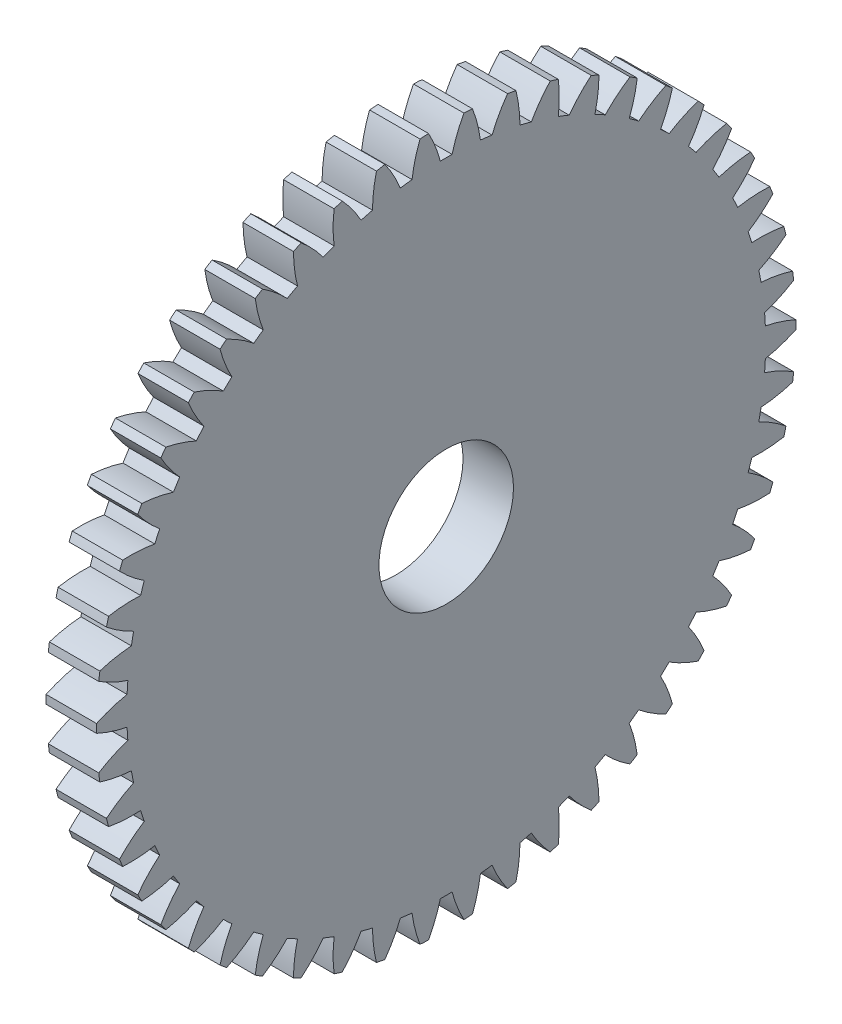
SolidWorks part; units mm, degrees
ref_plane "Plane1" through (0, 0, 0) normal (0, 0, 1) x (1, 0, 0)
ref_plane "Plane2" through (0, 0, 0) normal (0, 1, 0) x (1, 0, 0)
ref_plane "Plane3" through (0, 0, 0) normal (1, 0, 0) x (0, 0, -1)
sketch "HoldingSke" plane through (0, 0, 0) normal (0, 1, 0) x (1, 0, 0)
  line L0 (0, 0) -> (0.8035, -0.9576)
  line L1 (-15, 0) -> (100, 0) construction
  line L2 (0, 0) -> (-2.1039, 2.3779)
  line L3 (0, 0) -> (-11.863, 4.5341)
  line L4 (0, 0) -> (5.5511, 6.6156)
  line L5 (0, 0) -> (-46.8476, -17.4728)
  line L6 (0, 0) -> (-2.4869, -1.6779)
  line L7 (-2.1039, 2.3779) -> (8.6586, 51.2059)
  line L8 (-76.2, 54.61) -> (-75.9, 54.61)
  line L9 (-71.009, 38.7566) -> (-53.1078, 45.2721)
  line L10 (-76.2, 71.12) -> (104.1128, 71.12)
  line L11 (0, 0) -> (-3, 0)
  line L12 (-76.2, 101.6) -> (-76.17, 101.6)
  line L13 (24.9733, 27.94) -> (52.9518, 28.4284)
  line L14 (24.9733, 27.94) -> (24.9743, 27.94)
  line L15 (24.9733, 27.94) -> (100.4006, 29.5858)
  line L16 (-63.627, -0.8) -> (-12.827, -0.8)
  circle A0 centre (0, 0) radius 1
  circle A1 centre (0, 0) radius 18.999
  circle A2 centre (0, 0) radius 37.5
  circle A3 centre (0, 0) radius 1
  dimension "MHD" = 37.998
  dimension "Hub_dia" = 75
  dimension "Bore" = 2
  dimension "MBD" = 2
  dimension "Num_teeth" = 50
  dimension "Pitch" = 1.25
  dimension "Overall_len" = 50
  dimension "Show_teeth" = 50
  dimension "Thickness" = 3
  dimension "OAL" = 50.0001
  dimension "T_dim" = 0.3
  dimension "Ap" = 20
  dimension "H" = 19.05
  dimension "Pitch_radius" = 180.3128
  dimension "Width" = 3
  dimension "Backlash" = 0.03
  dimension "Addendum_fac" = 1
  dimension "Dedendum_fac" = 1.25
  dimension "Clearance_fac" = 0.25
  dimension "Dedendum_add" = 0.001
  dimension "Module" = 0.8
sketch "BasProSke" plane through (0, 0, 0) normal (0, 1, 0) x (1, 0, 0)
  line L0 (-10, 0) -> (60, 0) construction
  line L1 (0, 0) -> (0, 20.8)
  line L2 (0, 0) -> (3, 0)
  line L3 (3, 0) -> (3, 20.8)
  line L4 (3, 20.8) -> (0, 20.8)
  dimension "Thickness" = 3
  dimension "Diameter" = 41.6
revolve "Base-Revolve" add sketch "BasProSke" angle 360 about L0
sketch "TooCutSke" plane through (0, 0, 0) normal (1, 0, 0) x (0, 0, -1)
  line L1 (0, 0) -> (0, 107) construction
  line L2 (0, 0) -> (-0.6807, 19.9884) construction
  line L3 (0, 0) -> (-2.5106, 39.9045) construction
  line L4 (-0.6807, 19.9884) -> (-1.2553, 19.9523) construction
  arc A0 (0.3494, 18.9958) -> (-0.3494, 18.9958) centre (0, 0) ccw
  arc A1 (1.0655, 20.7981) -> (-1.0655, 20.7981) centre (0, 0) ccw
  circle A2 centre (0, 0) radius 20 construction
  circle A3 centre (0, 0) radius 18.7939 construction
  arc A4 (-0.3494, 18.9958) -> (-1.0655, 20.7981) centre (-8.0873, 16.9648) ccw
  arc A5 (1.0655, 20.7981) -> (0.3494, 18.9958) centre (8.0873, 16.9648) ccw
  dimension "Root_dia" = 37.998
  dimension "Overcut_dia" = 41.6508
  dimension "Pitch_dia" = 40
  dimension "Base_dia" = 37.5877
  dimension "Flank_rad" = 8
  dimension "Half_ang" = 3.6
  dimension "Half_CT" = 0.5757
extrude "ToothCut" cut sketch "TooCutSke" along normal through all
fillet "Breaks" [suppressed] radius 0.016
fillet "RootFillets" [suppressed] radius 0.201
pattern_circular "TeethCuts" count 50 every 7.2 about axis through (-10, 0, 0) along (1, 0, 0) of "ToothCut", "RootFillets", "Breaks"
sketch "HubNeaOneSke" plane through (0, 0, 0) normal (-1, 0, 0) x (0, 0, 1)
  circle A0 centre (0, 0) radius 18.999
  dimension "Diameter" = 37.998
extrude "HubNearOne" [suppressed] add sketch "HubNeaOneSke" along normal blind 47.0001
sketch "HubNeaBotSke" plane through (0, 0, 0) normal (-1, 0, 0) x (0, 0, 1)
  circle A0 centre (0, 0) radius 18.999
  dimension "Diameter" = 37.998
extrude "HubNearBoth" [suppressed] add sketch "HubNeaBotSke" along normal blind 23.5
ref_plane "FarPln" through (3, 0, 0) normal (1, 0, 0) x (0, 0, -1)
sketch "HubFarSke" plane through (3, 0, 0) normal (1, 0, 0) x (0, 0, -1)
  circle A0 centre (0, 0) radius 18.999
  dimension "Diameter" = 37.998
extrude "HubFar" [suppressed] add sketch "HubFarSke" along normal blind 23.5
sketch "BorSke" plane through (0, 0, 0) normal (1, 0, 0) x (0, 0, -1)
  circle A0 centre (0, 0) radius 1
  dimension "Diameter" = 2
extrude "Bore" cut sketch "BorSke" along normal mid plane 100.0001
sketch "KeySke" plane through (0, 0, 0) normal (1, 0, 0) x (0, 0, -1)
  line L0 (-0.4, 0) -> (-0.4, 1.3)
  line L1 (-0.4, 1.3) -> (0.4, 1.3)
  line L2 (0.4, 1.3) -> (0.4, 0)
  line L3 (0, 0) -> (0, 34) construction
  line L4 (-0.4, 0) -> (0.4, 0)
  dimension "Offset" = 1.3
  dimension "Width" = 0.8
extrude "Keyway" [suppressed] cut sketch "KeySke" along normal mid plane 100.0001
pattern_circular "Keyway2" [suppressed] count 2 every 90 about axis through (-10, 0, 0) along (1, 0, 0)
sketch "Sketch1" plane through (3, 0, 0) normal (1, 0, 0) x (0, 0, -1)
  circle A1 centre (0, 0) radius 4
extrude "Cut-Extrude2" cut sketch "Sketch1" against normal blind 3 contours A1
equation "' \"Module@HoldingSke\" = 6.35"
equation "' \"Num_teeth@HoldingSke\" = 12"
equation "' \"Ap@HoldingSke\" =  20"
equation "' \"Ap@HoldingSke\" = 20"
equation "' \"Width@HoldingSke\" = 0.5 * 25.4"
equation "' \"Hub_dia@HoldingSke\"= 1 * 25.4"
equation "' \"Hub_dia@HoldingSke\" = 1 * 25.4"
equation "' \"Overall_len@HoldingSke\" = 1.0 * 25.4"
equation "' \"Bore@HoldingSke\" = 0.75 * 25.4"
equation "' \"T_dim@HoldingSke\" = 0.1 * 25.4"
equation "' \"Width@KeySke\" = 0.25 * 25.4"
equation "' \"Show_teeth@HoldingSke\" = 13"
equation "' \"Backlash@HoldingSke\" = 0.009 * 25.4"
equation "' \"Addendum_fac@HoldingSke\" = 1.0"
equation "' \"Dedendum_fac@HoldingSke\" = 1.25"
equation "' \"Dedendum_add@HoldingSke\" = 0.00005 * 25.4"
equation "' \"Clearance_fac@HoldingSke\" = 0.25"
equation "\"Pitch@HoldingSke\" = 1 / \"Module@HoldingSke\""
equation "\"Overcut_dia@TooCutSke\" = (\"Num_teeth@HoldingSke\" + 2 * \"Addendum_fac@HoldingSke\") / \"Pitch@HoldingSke\" + 0.002 * 25.4"
equation "\"Pitch_dia@TooCutSke\" = \"Num_teeth@HoldingSke\" / \"Pitch@HoldingSke\""
equation "\"Base_dia@TooCutSke\" = \"Num_teeth@HoldingSke\" / \"Pitch@HoldingSke\" * cos((\"Ap@HoldingSke\"  * 3.14159265 / 180))"
equation "\"Root_dia@TooCutSke\" = (\"Num_teeth@HoldingSke\" + 2) / \"Pitch@HoldingSke\" - 2 * (\"Addendum_fac@HoldingSke\" + \"Dedendum_fac@HoldingSke\") / \"Pitch@HoldingSke\" - \"Dedendum_add@HoldingSke\" * 2"
equation "\"Half_ang@TooCutSke\" = 180 / \"Num_teeth@HoldingSke\""
equation "\"Half_CT@TooCutSke\" = \"Num_teeth@HoldingSke\" / \"Pitch@HoldingSke\" * sin((3.14159265 / 2 / \"Num_teeth@HoldingSke\")) / 2 - 7 * \"Backlash@HoldingSke\" / 4"
equation "\"Flank_rad@TooCutSke\" = \"Num_teeth@HoldingSke\" / \"Pitch@HoldingSke\" / 5"
equation "\"Radius@RootFillets\" = \"Clearance_fac@HoldingSke\" / \"Pitch@HoldingSke\" + \"Dedendum_add@HoldingSke\""
equation "\"Break_rad@Breaks\" = 0.02 / \"Pitch@HoldingSke\""
equation "\"Thickness@HoldingSke\" = \"Width@HoldingSke\""
equation "\"OAL@HoldingSke\" = \"Thickness@HoldingSke\""
equation "\"MHD@HoldingSke\" = (\"Num_teeth@HoldingSke\" + 2) / \"Pitch@HoldingSke\" - 2 * (\"Addendum_fac@HoldingSke\" + \"Dedendum_fac@HoldingSke\")  / \"Pitch@HoldingSke\" - \"Dedendum_add@HoldingSke\" * 2"
equation "\"MBD@HoldingSke\" = (\"Num_teeth@HoldingSke\" + 2) / \"Pitch@HoldingSke\" - 2 * (\"Addendum_fac@HoldingSke\" + \"Dedendum_fac@HoldingSke\")  / \"Pitch@HoldingSke\" - \"Dedendum_add@HoldingSke\" * 2 - 0.002 * 25.4"
equation "\"MHD@HoldingSke\" = ((sgn( \"MHD@HoldingSke\" - \"Hub_dia@HoldingSke\" )-1)*( \"MHD@HoldingSke\" - \"Hub_dia@HoldingSke\" ))/-2+ \"Hub_dia@HoldingSke\""
equation "\"MBD@HoldingSke\" = ((sgn( \"MBD@HoldingSke\" - \"Bore@HoldingSke\" )-1)*( \"MBD@HoldingSke\" - \"Bore@HoldingSke\" ))/-2+ \"Bore@HoldingSke\""
equation "\"OAL@HoldingSke\" = ((sgn( \"OAL@HoldingSke\" - \"Overall_len@HoldingSke\" )+1)*( \"OAL@HoldingSke\" - \"Overall_len@HoldingSke\" ))/2 + \"Overall_len@HoldingSke\" + 0.000002 * 25.4"
equation "\"Num_teeth@TeethCuts\" = int( \"Show_teeth@HoldingSke\" ) + 1"
equation "\"Num_teeth@TeethCuts\" = ((sgn( \"Num_teeth@TeethCuts\" - \"Num_teeth@HoldingSke\" )-1)*( \"Num_teeth@TeethCuts\" - \"Num_teeth@HoldingSke\" ))/-2+ \"Num_teeth@HoldingSke\""
equation "\"Num_teeth@TeethCuts\" = ((sgn( \"Num_teeth@TeethCuts\" - 2.0)+1)*( \"Num_teeth@TeethCuts\" - 2.0))/2 +2.0"
equation "\"Angle@TeethCuts\" = 360.0 / \"Num_teeth@HoldingSke\""
equation "\"Diameter@BasProSke\" = (\"Num_teeth@HoldingSke\" + 2 * \"Addendum_fac@HoldingSke\") / \"Pitch@HoldingSke\""
equation "\"Thickness@BasProSke\"  = \"Thickness@HoldingSke\""
equation "' \"Fillet_rad@BasProSke\" =  \"Thickness@HoldingSke\" * 0.05"
equation "' \"Fillet_rad@BasProSke\" = \"Thickness@HoldingSke\" * 0.05"
equation "\"MHD@HoldingSke\" = ((sgn( \"MHD@HoldingSke\" - \"Root_dia@TooCutSke\" )-1)*( \"MHD@HoldingSke\" - \"Root_dia@TooCutSke\" ))/-2+ \"Root_dia@TooCutSke\""
equation "\"Diameter@HubNeaOneSke\" = \"MHD@HoldingSke\""
equation "\"Length@HubNearOne\" = \"OAL@HoldingSke\" - \"Thickness@BasProSke\""
equation "\"Diameter@HubNeaBotSke\" = \"MHD@HoldingSke\""
equation "\"Length@HubNearBoth\" = ( \"OAL@HoldingSke\" - \"Thickness@BasProSke\" ) / 2.0"
equation "\"Thickness@FarPln\" = \"Thickness@BasProSke\""
equation "\"Diameter@HubFarSke\" = \"MHD@HoldingSke\""
equation "\"Length@HubFar\" = ( \"OAL@HoldingSke\" - \"Thickness@BasProSke\" ) / 2.0"
equation "\"Diameter@BorSke\" = \"MBD@HoldingSke\""
equation "\"D1@Bore\" = \"OAL@HoldingSke\" * 2.0"
equation "\"D1@Keyway\" = \"OAL@HoldingSke\" * 2.0"
equation "\"Offset@KeySke\" = \"T_dim@HoldingSke\" + \"MBD@HoldingSke\" / 2.0"
